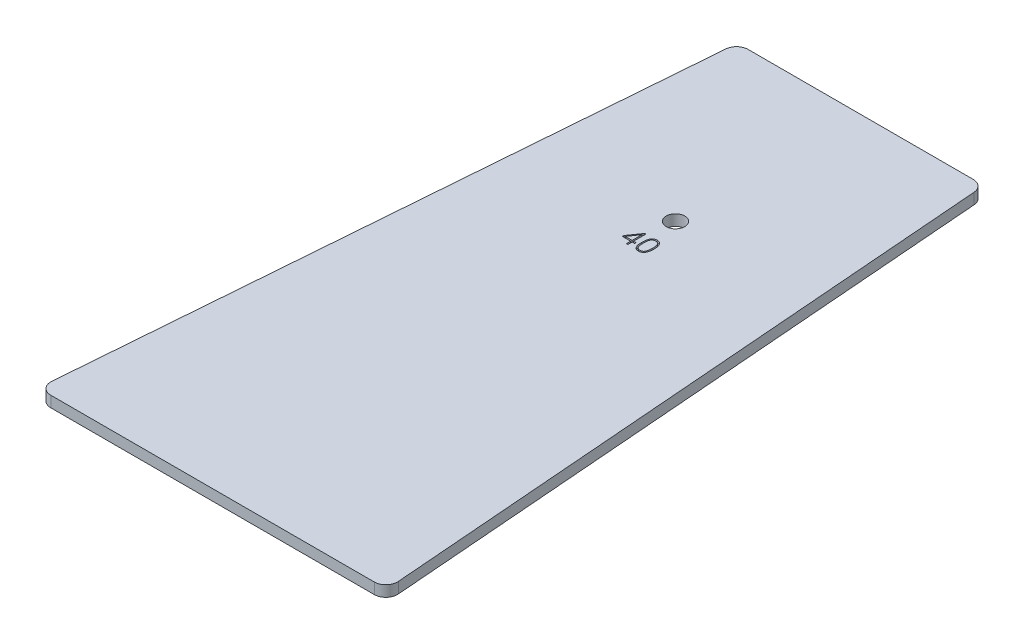
SolidWorks part; units mm, degrees
material "Acrylic (Medium-high impact)"
ref_plane "Front Plane" through (0, 0, 0) normal (0, 0, 1) x (1, 0, 0)
ref_plane "Top Plane" through (0, 0, 0) normal (0, 1, 0) x (1, 0, 0)
ref_plane "Right Plane" through (0, 0, 0) normal (1, 0, 0) x (0, 0, -1)
sketch "Sketch1" plane through (0, 0, 0) normal (0, 1, 0) x (1, 0, 0)
  line L0 (0, 0) -> (0, -355.6) construction
  line L1 (-67.6275, 0) -> (67.6275, 0)
  line L2 (67.6275, 0) -> (95.6138, -355.6)
  line L3 (95.6138, -355.6) -> (-95.6138, -355.6)
  line L4 (-67.6275, 0) -> (-95.6138, -355.6)
  dimension "D1" = 355.6
  dimension "D2" = 9
  dimension "D3" = 135.255
extrude "Boss-Extrude1" add sketch "Sketch1" along normal blind 5.9944
sketch "Sketch2" plane through (0, 5.9944, 0) normal (0, 1, 0) x (1, 0, 0)
  line L0 (0, 0) -> (0, -101.6) construction
  line L1 (67.6275, 0) -> (-67.6275, 0) construction
  circle A0 centre (0, -101.6) radius 5.08
  dimension "D2" = 10.16
  dimension "D1" = 101.6
extrude "Cut-Extrude1" cut sketch "Sketch2" against normal through all
sketch "Sketch3" plane through (0, 5.9944, 0) normal (0, 1, 0) x (1, 0, 0)
  line L0 (0, 0) -> (0, -114.3) construction
  line L1 (-7.62, -125.73) -> (7.62, -125.73) construction
  line L2 (-7.62, -125.73) -> (-7.62, -114.3) construction
  line L3 (-7.62, -114.3) -> (7.62, -114.3) construction
  line L4 (7.62, -125.73) -> (7.62, -114.3) construction
  line L5 (67.6275, 0) -> (-67.6275, 0) construction
  text T0 "40"
  dimension "D1" = 11.43
  dimension "D2" = 15.24
  dimension "D3" = 114.3
extrude "Cut-Extrude2" cut sketch "Sketch3" against normal blind 1.27
fillet "Fillet1" radius 6.35 4 edges at (95.6138, 2.9972, 355.6) (-95.6138, 2.9972, 355.6) (-67.6275, 2.9972, 0) (67.6275, 2.9972, 0)
